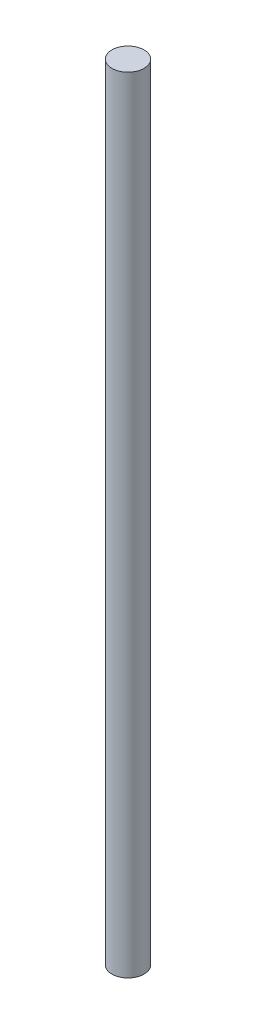
SolidWorks part; units mm, degrees
ref_plane "Front Plane" through (0, 0, 0) normal (0, 0, 1) x (1, 0, 0)
ref_plane "Top Plane" through (0, 0, 0) normal (0, 1, 0) x (1, 0, 0)
ref_plane "Right Plane" through (0, 0, 0) normal (1, 0, 0) x (0, 0, -1)
sketch "Sketch1" plane through (0, 0, 0) normal (0, 1, 0) x (1, 0, 0)
  circle A0 centre (0, 0) radius 2.25
  dimension "D1" = 4.5
extrude "Boss-Extrude1" add sketch "Sketch1" along normal blind 110
